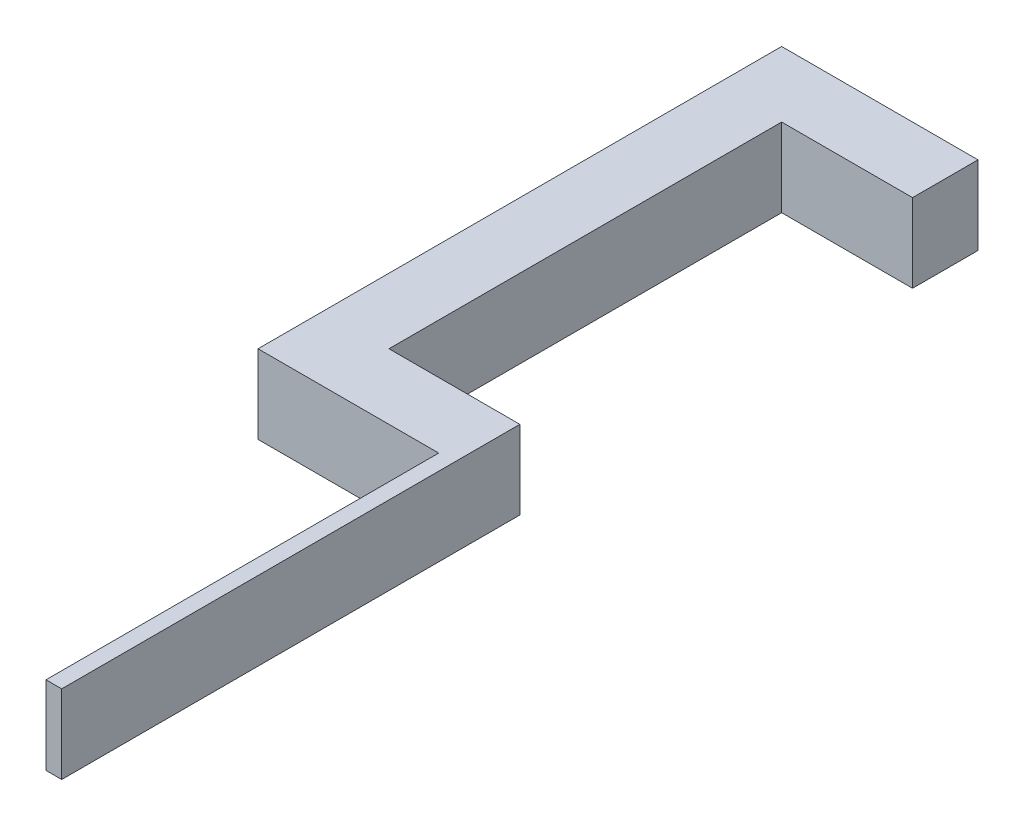
SolidWorks part; units mm, degrees
ref_plane "前视" through (0, 0, 0) normal (0, 0, 1) x (1, 0, 0)
ref_plane "上视" through (0, 0, 0) normal (0, 1, 0) x (1, 0, 0)
ref_plane "右视" through (0, 0, 0) normal (1, 0, 0) x (0, 0, -1)
sketch "Sketch1" plane through (0, 0, 0) normal (0, 1, 0) x (1, 0, 0)
  line L0 (0, 20) -> (0, 17.5)
  line L1 (0, 0) -> (-7.5, 0) construction
  line L2 (0, 0) -> (0, 20) construction
  line L3 (0, 20) -> (-7.5, 20)
  line L4 (-7.5, 0) -> (-7.5, 20)
  line L5 (0, 17.5) -> (-5, 17.5)
  line L6 (-5, 17.5) -> (-5, 2.5)
  line L7 (-5, 2.5) -> (0, 2.5)
  line L8 (0, 2.5) -> (0, -15)
  line L9 (0, -15) -> (-0.6, -15)
  line L10 (-0.6, -15) -> (-0.6, 0)
  line L11 (-0.6, 0) -> (-7.5, 0)
  line L12 (0, 17.5) -> (0, 2.5) construction
  point P10 (0, 10)
  dimension "D1" = 2.5
  dimension "D2" = 2.5
  dimension "D3" = 15
  dimension "D4" = 5
  dimension "D5" = 0.6
  dimension "D6" = 15
extrude "Boss-Extrude1" add sketch "Sketch1" along normal blind 3
